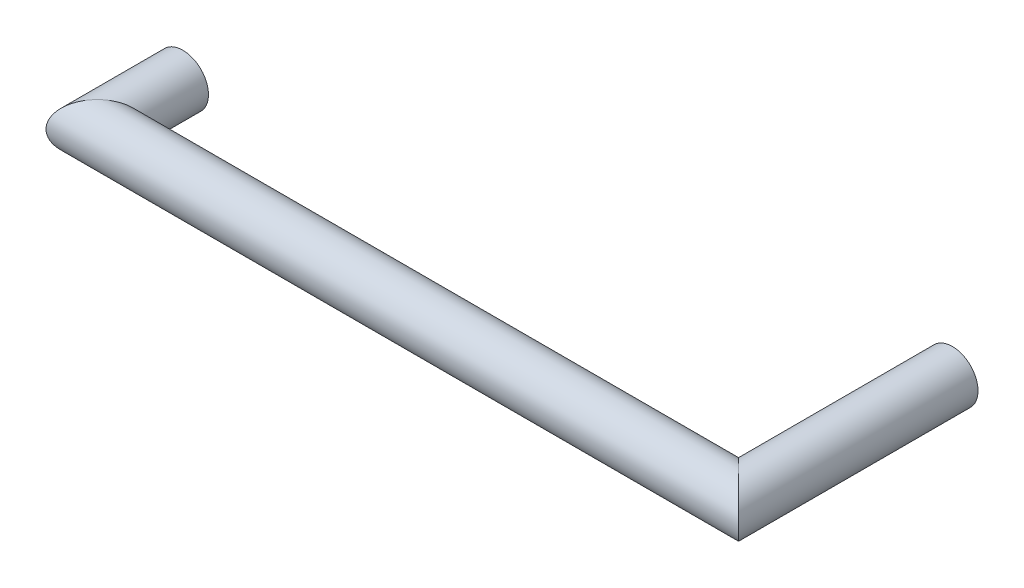
SolidWorks part; units mm, degrees
material "Cast Stainless Steel"
ref_plane "Front Plane" through (0, 0, 0) normal (0, 0, 1) x (1, 0, 0)
ref_plane "Top Plane" through (0, 0, 0) normal (0, 1, 0) x (1, 0, 0)
ref_plane "Right Plane" through (0, 0, 0) normal (1, 0, 0) x (0, 0, -1)
sketch "Sketch2" plane through (0, 0, 0) normal (0, 1, 0) x (1, 0, 0)
  line L0 (-7.5, 0) -> (7.5, 0)
  line L1 (-7.5, 0) -> (-7.5, 2)
  line L2 (7.5, 0) -> (7.5, 5)
  point P4 (0, 0)
  dimension "D1" = 15
  dimension "D2" = 2
  dimension "D3" = 5
ref_plane "Plane1" through (-7.5, 0, -2) normal (0, 0, -1) x (-1, 0, 0)
sketch "Sketch3" plane through (-7.5, 0, -2) normal (0, 0, -1) x (-1, 0, 0)
  circle A1 centre (0, 0) radius 0.6
  point P0 (0, 0)
  dimension "D1" = 1.2
sweep "Sweep1" add profiles "Sketch3" path "Sketch2"
